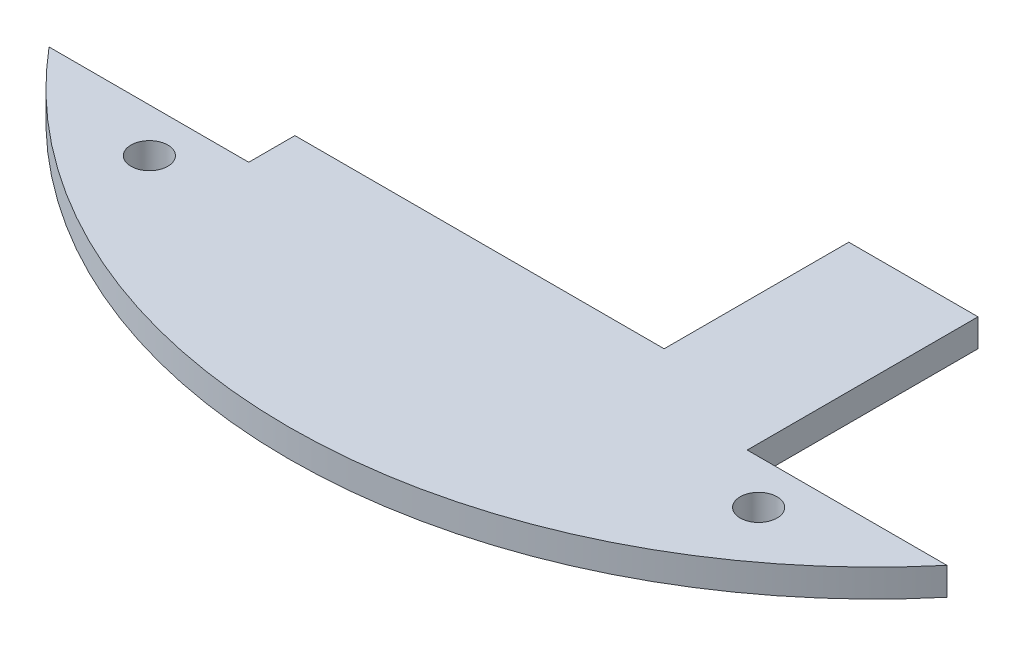
SolidWorks part; units mm, degrees
ref_plane "Front Plane" through (0, 0, 0) normal (0, 0, 1) x (1, 0, 0)
ref_plane "Top Plane" through (0, 0, 0) normal (0, 1, 0) x (1, 0, 0)
ref_plane "Right Plane" through (0, 0, 0) normal (1, 0, 0) x (0, 0, -1)
sketch "Sketch1" plane through (0, 0, 0) normal (0, 1, 0) x (1, 0, 0)
  line L0 (27, -10.8233) -> (27, 10) construction
  line L1 (0, 0) -> (20, 0)
  line L2 (0, 0) -> (0, -2.5)
  line L3 (13.5, -13.8363) -> (13.5, 0) construction
  line L4 (27, 0) -> (27, -2.5)
  line L5 (27, -2.5) -> (37.8176, -2.5)
  line L6 (0, -2.5) -> (-10.8176, -2.5)
  line L7 (27, 0) -> (27, 10)
  line L8 (27, 10) -> (20, 10)
  line L9 (20, 0) -> (20, 10)
  line L10 (37, -2.5) -> (37, -3.4361) construction
  arc A0 (27, -10.8233) -> (0, -10.8233) centre (13.5, 17.9137) cw
  arc A1 (-14.5336, 3.0079) -> (0, -10.8233) centre (13.5, 17.9137) ccw construction
  arc A2 (27, -10.8233) -> (41.5336, 3.0079) centre (13.5, 17.9137) ccw construction
  arc A3 (27, -10.8233) -> (37.8176, -2.5) centre (13.5, 17.9137) ccw
  circle A4 centre (30, -4.882) radius 1 construction
  circle A5 centre (30, -4.882) radius 1
  circle A6 centre (-3, -4.882) radius 1
  arc A7 (0, -10.8233) -> (-10.8176, -2.5) centre (13.5, 17.9137) cw
  dimension "D1" = 2.5
  dimension "D2" = 10
extrude "Boss-Extrude1" add sketch "Sketch1" along normal blind 1.5
